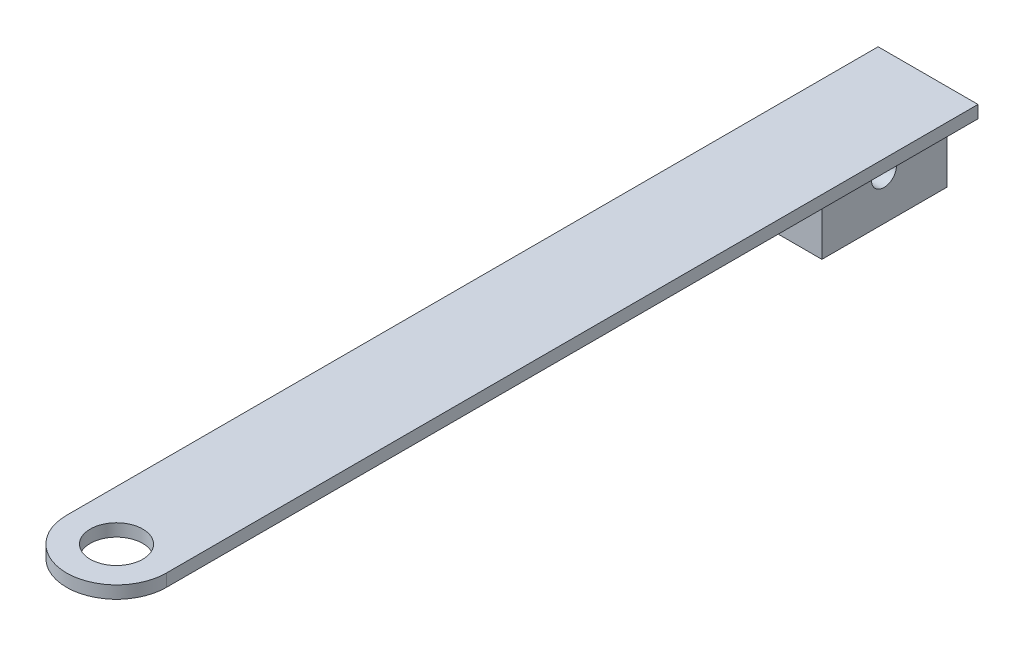
SolidWorks part; units mm, degrees
ref_plane "Front Plane" through (0, 0, 0) normal (0, 0, 1) x (1, 0, 0)
ref_plane "Top Plane" through (0, 0, 0) normal (0, 1, 0) x (1, 0, 0)
ref_plane "Right Plane" through (0, 0, 0) normal (1, 0, 0) x (0, 0, -1)
sketch "Sketch1" plane through (0, 0, 0) normal (0, 1, 0) x (1, 0, 0)
  circle A0 centre (0, 0) radius 2.667
  circle A1 centre (0, 0) radius 5.08
  dimension "D1" = 5.334
  dimension "D2" = 10.16
extrude "Boss-Extrude1" add sketch "Sketch1" along normal blind 1.27 contours A1 A0
sketch "Sketch5" plane through (0, 0, 0) normal (0, -1, 0) x (-1, 0, 0)
  line L0 (-5.08, 0) -> (-5.08, 82.55)
  line L1 (-5.08, 82.55) -> (5.08, 82.55)
  line L2 (5.08, 82.55) -> (5.08, 0)
  circle A0 centre (0, 0) radius 5.08 construction
  arc A1 (5.08, 0) -> (-5.08, 0) centre (0, 0) ccw
  dimension "D3" = 5.08
  dimension "D1" = 82.55
  dimension "D2" = 10.16
extrude "Boss-Extrude5" add sketch "Sketch5" against normal up to surface (1.27 mm away) up to face at (0, 1.27, 2.667)
sketch "Sketch6" plane through (0, 0, 0) normal (0, -1, 0) x (1, 0, 0)
  line L1 (-5.08, -82.55) -> (1.905, -82.55)
  line L2 (-5.08, -82.55) -> (-5.08, -69.85)
  line L3 (-5.08, -69.85) -> (1.905, -69.85)
  line L4 (1.905, -82.55) -> (1.905, -69.85)
  point P7 (0, 0)
  dimension "D1" = 6.985
  dimension "D2" = 12.7
extrude "Boss-Extrude6" add sketch "Sketch6" along normal blind 7.62
sketch "Sketch7" plane through (1.905, 0, 0) normal (1, 0, 0) x (0, 0, -1)
  line L0 (82.55, 0) -> (0, 0) construction
  line L1 (82.55, -7.62) -> (82.55, 0) construction
  circle A0 centre (76.1577, -3.175) radius 1.27
  point P3 (0, 0)
  dimension "D2" = 2.54
  dimension "D3" = 6.3923
  dimension "D1" = 3.175
extrude "Cut-Extrude2" cut sketch "Sketch7" against normal up to next contours A0
